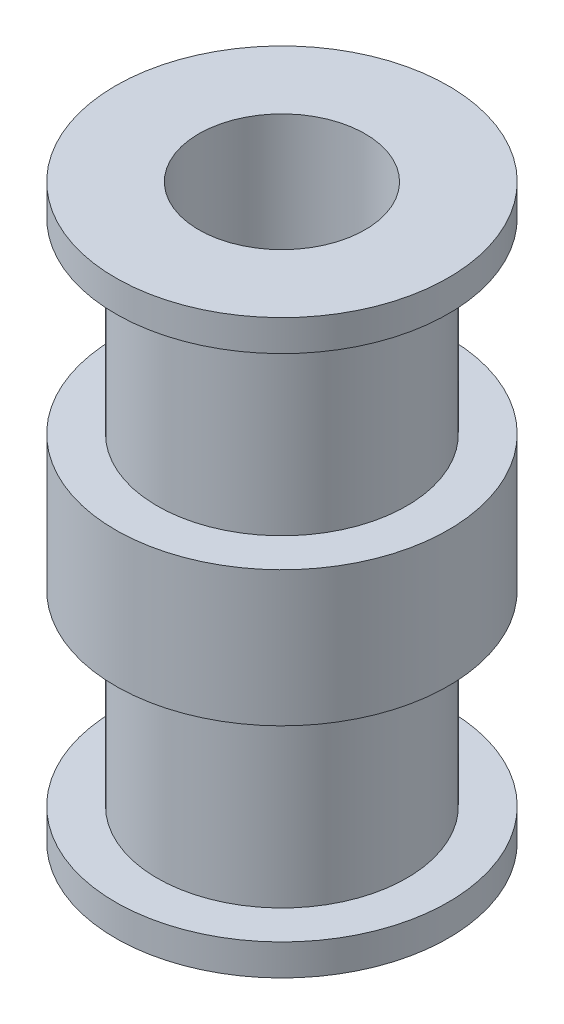
SolidWorks part; units mm, degrees
ref_plane "Front Plane" through (0, 0, 0) normal (0, 0, 1) x (1, 0, 0)
ref_plane "Top Plane" through (0, 0, 0) normal (0, 1, 0) x (1, 0, 0)
ref_plane "Right Plane" through (0, 0, 0) normal (1, 0, 0) x (0, 0, -1)
sketch "Sketch1" plane through (0, 0, 0) normal (0, 0, 1) x (1, 0, 0)
  line L0 (0, 291.2678) -> (0, 5) construction
  line L1 (0, -22.5) -> (0, -291.5464) construction
  line L2 (0, 5) -> (-8, 5)
  line L4 (-6, 3.5) -> (-8, 3.5)
  line L5 (-8, 5) -> (-8, 3.5)
  line L9 (-6, 3.5) -> (-6, -5.5)
  line L10 (-6, -5.5) -> (-8, -5.5)
  line L12 (-6, -12) -> (-8, -12)
  line L13 (-8, -5.5) -> (-8, -12)
  line L17 (-6, -12) -> (-6, -21)
  line L18 (-6, -21) -> (-8, -21)
  line L20 (0, -22.5) -> (-8, -22.5)
  line L21 (-8, -21) -> (-8, -22.5)
  line L22 (0, 5) -> (0, -22.5)
  point P5 (0, -12.5604)
  point P8 (-8, -8.75)
  point P11 (0, -8.75)
  dimension "D1" = 6.5
  dimension "D2" = 27.5
  dimension "D3" = 9
  dimension "D4" = 9
  dimension "D5" = 8
  dimension "D6" = 5
  dimension "D7" = 6
revolve "Revolve1" add sketch "Sketch1" angle 360 about L0
sketch "Sketch2" plane through (0, 5, 0) normal (0, 1, 0) x (1, 0, 0)
  circle A0 centre (0, 0) radius 4
  dimension "D1" = 8
extrude "Cut-Extrude1" cut sketch "Sketch2" against normal up to next
sketch "Sketch3" plane through (0, 0, 0) normal (0, 0, 1) x (1, 0, 0)
  line L0 (0, 0) -> (0, -10.9246) construction
  circle A0 centre (0, -8.8201) radius 1.25
  dimension "D1" = 2.5
extrude "Cut-Extrude2" cut sketch "Sketch3" against normal blind 10
pattern_circular "CirPattern1" count 2 every 90 about axis through (0, -22.5, 0) along (0, -1, 0) of "Cut-Extrude2"
